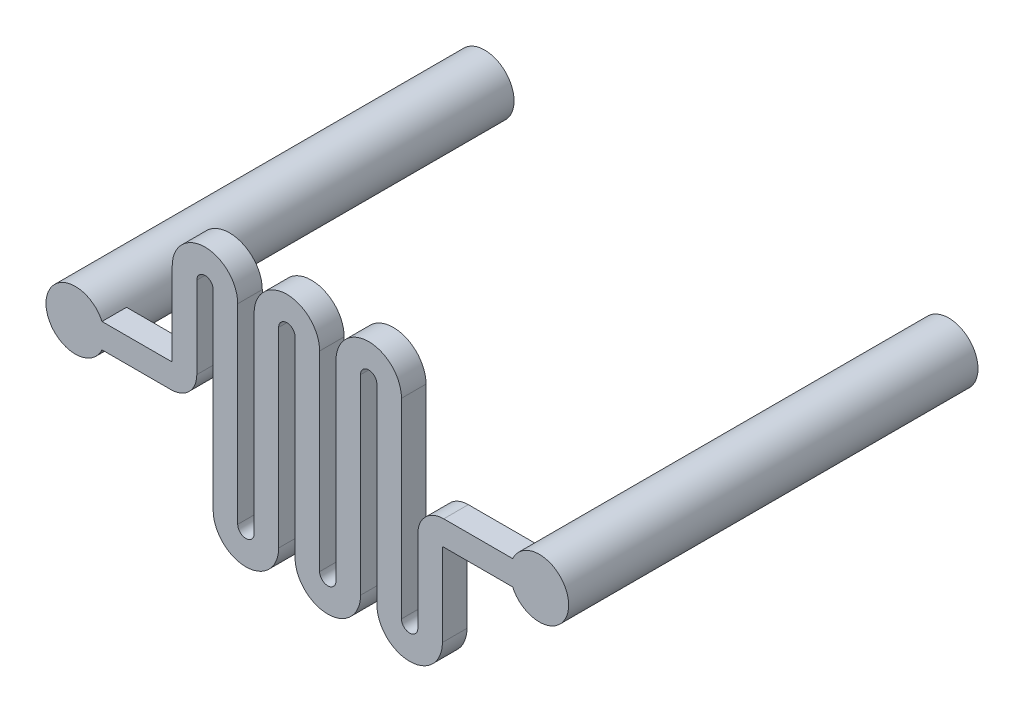
SolidWorks part; units mm, degrees
ref_plane "Front Plane" through (0, 0, 0) normal (0, 0, 1) x (1, 0, 0)
ref_plane "Top Plane" through (0, 0, 0) normal (0, 1, 0) x (1, 0, 0)
ref_plane "Right Plane" through (0, 0, 0) normal (1, 0, 0) x (0, 0, -1)
sketch "Sketch2" plane through (0, 0, 0) normal (0, 0, 1) x (1, 0, 0)
  line L3 (-20.5, -0.9) -> (-13.5, -0.9)
  line L6 (-11.6, 1) -> (-11.6, 7)
  line L9 (-10.4, 7) -> (-10.4, 0)
  line L12 (-10.4, 0) -> (-10.4, -7)
  line L15 (-5.6, -7) -> (-5.6, 0)
  line L18 (-5.6, 0) -> (-5.6, 7)
  line L21 (-4.4, 7) -> (-4.4, 0)
  line L22 (-4.4, 0) -> (-4.4, -7)
  line L23 (0.4, -7) -> (0.4, 0)
  line L24 (0.4, 0) -> (0.4, 7)
  line L25 (1.6, 7) -> (1.6, 0)
  line L26 (1.6, 0) -> (1.6, -7)
  line L27 (6.4, -7) -> (6.4, -1)
  line L28 (6.5, -0.9) -> (13.5, -0.9)
  line L29 (-20.5, 0.9) -> (-13.5, 0.9)
  line L30 (-13.4, 1) -> (-13.4, 7)
  line L31 (-8.6, 7) -> (-8.6, 0)
  line L32 (-8.6, 0) -> (-8.6, -7)
  line L33 (-7.4, -7) -> (-7.4, 0)
  line L34 (-7.4, 0) -> (-7.4, 7)
  line L35 (-2.6, 7) -> (-2.6, 0)
  line L36 (-2.6, 0) -> (-2.6, -7)
  line L37 (-1.4, -7) -> (-1.4, 0)
  line L38 (-1.4, 0) -> (-1.4, 7)
  line L39 (3.4, 7) -> (3.4, 0)
  line L40 (3.4, 0) -> (3.4, -7)
  line L41 (4.6, -7) -> (4.6, -1)
  line L42 (6.5, 0.9) -> (13.5, 0.9)
  arc A8 (-11.6, 1) -> (-13.5, -0.9) centre (-13.5, 1) cw
  arc A9 (-11.6, 7) -> (-10.4, 7) centre (-11, 7) cw
  arc A10 (-10.4, -7) -> (-5.6, -7) centre (-8, -7) ccw
  arc A11 (-5.6, 7) -> (-4.4, 7) centre (-5, 7) cw
  arc A12 (-4.4, -7) -> (0.4, -7) centre (-2, -7) ccw
  arc A13 (0.4, 7) -> (1.6, 7) centre (1, 7) cw
  arc A14 (1.6, -7) -> (6.4, -7) centre (4, -7) ccw
  arc A15 (6.4, -1) -> (6.5, -0.9) centre (6.5, -1) cw
  arc A16 (-13.4, 1) -> (-13.5, 0.9) centre (-13.5, 1) cw
  arc A17 (-13.4, 7) -> (-8.6, 7) centre (-11, 7) cw
  arc A18 (-8.6, -7) -> (-7.4, -7) centre (-8, -7) ccw
  arc A19 (-7.4, 7) -> (-2.6, 7) centre (-5, 7) cw
  arc A20 (-2.6, -7) -> (-1.4, -7) centre (-2, -7) ccw
  arc A21 (-1.4, 7) -> (3.4, 7) centre (1, 7) cw
  arc A22 (3.4, -7) -> (4.6, -7) centre (4, -7) ccw
  arc A23 (4.6, -1) -> (6.5, 0.9) centre (6.5, -1) cw
  arc A24 (-20.5, 0.9) -> (-20.5, -0.9) centre (-20.5, 0) ccw
  arc A25 (13.5, -0.9) -> (13.5, 0.9) centre (13.5, 0) ccw
  point P4 (0, 0)
  point P32 (5.5, 0)
  point P35 (-12.5, 0)
  dimension "D1" = 8
  dimension "D14" = 8
extrude "Boss-Extrude1" add sketch "Sketch2" along normal blind 1.8
ref_plane "Plane1" through (0, 0, 0) normal (0, 1, 0) x (1, 0, 0)
ref_plane "Plane2" through (0, 0, 0) normal (0, 1, 0) x (1, 0, 0)
sketch "Sketch3" plane through (0, 0, 0) normal (0, 1, 0) x (1, 0, 0)
  line L1 (-20.5, 28.2) -> (-22.65, 28.2)
  line L2 (-20.5, -1.8) -> (-20.5, 28.2)
  line L6 (-22.65, 28.2) -> (-22.65, -1.8)
  line L7 (-22.65, -1.8) -> (-20.5, -1.8)
  dimension "D1" = 2.15
  dimension "D4" = 30
sketch "Sketch4" plane through (0, 0, 0) normal (0, 1, 0) x (1, 0, 0)
  line L1 (13.5, 28.2) -> (15.65, 28.2)
  line L2 (13.5, -1.8) -> (13.5, 28.2)
  line L6 (15.65, 28.2) -> (15.65, -1.8)
  line L7 (15.65, -1.8) -> (13.5, -1.8)
  dimension "D1" = 2.15
  dimension "D4" = 30
revolve "Revolve1" add sketch "Sketch3" angle 360 about L2
revolve "Revolve2" add sketch "Sketch4" angle 360 about L2
sketch "Sketch5" plane through (0, 0, -28.2) normal (0, 0, -1) x (-1, 0, 0)
  circle A0 centre (-13.5, 0) radius 1.5
  circle A1 centre (20.5, 0) radius 1.5
  dimension "D1" = 3
  dimension "D2" = 3
extrude "Cut-Extrude1" cut sketch "Sketch5" against normal blind 28
